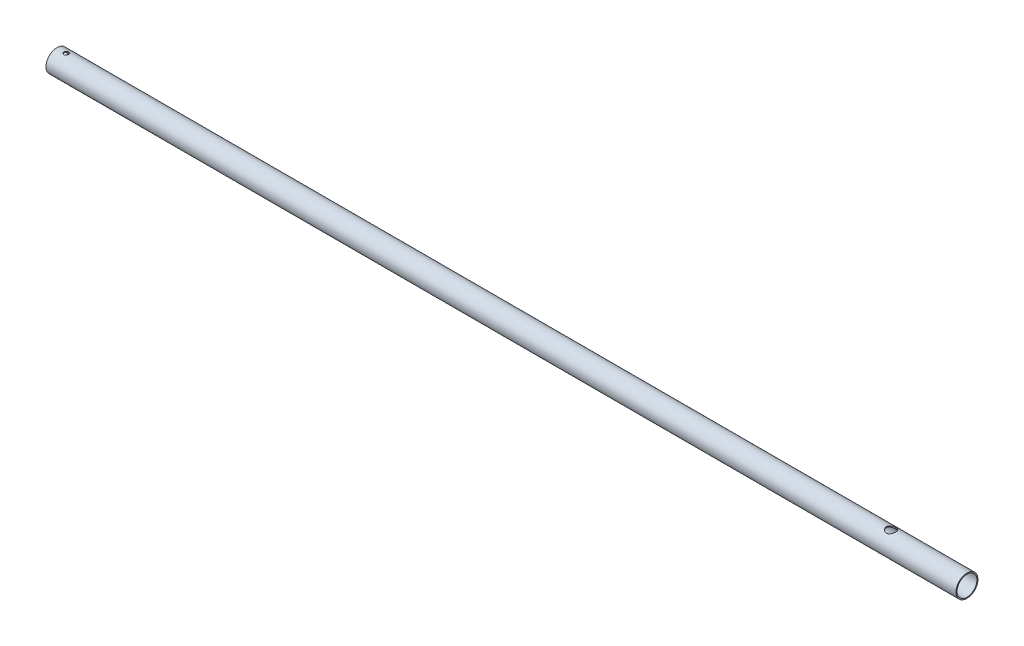
SolidWorks part; units mm, degrees
material "Galvanized Steel"
ref_plane "Front Plane" through (0, 0, 0) normal (0, 0, 1) x (1, 0, 0)
ref_plane "Top Plane" through (0, 0, 0) normal (0, 1, 0) x (1, 0, 0)
ref_plane "Right Plane" through (0, 0, 0) normal (1, 0, 0) x (0, 0, -1)
sketch "Sketch3" plane through (0, 0, 0) normal (1, 0, 0) x (0, 0, -1)
  circle A0 centre (0, 0) radius 13.3223
  circle A1 centre (0, 0) radius 14.7701
  dimension "D1" = 26.6446
  dimension "D2" = 29.5402
extrude "Boss-Extrude1" add sketch "Sketch3" along normal blind 1219.2
ref_plane "Plane2" through (0, -14.7701, 0) normal (0, -1, 0) x (-1, 0, 0)
sketch "Sketch6" plane through (0, -14.7701, 0) normal (0, -1, 0) x (-1, 0, 0)
  line L0 (0, -14.7701) -> (0, 14.7701) construction
  line L1 (-1219.2, 14.7701) -> (-1219.2, -14.7701) construction
  circle A0 centre (-1117.6, 0) radius 6.35
  circle A1 centre (-12.7, 0) radius 3.175
  dimension "D1" = 12.7
  dimension "D2" = 101.6
extrude "Cut-Extrude2" cut sketch "Sketch6" against normal through all
